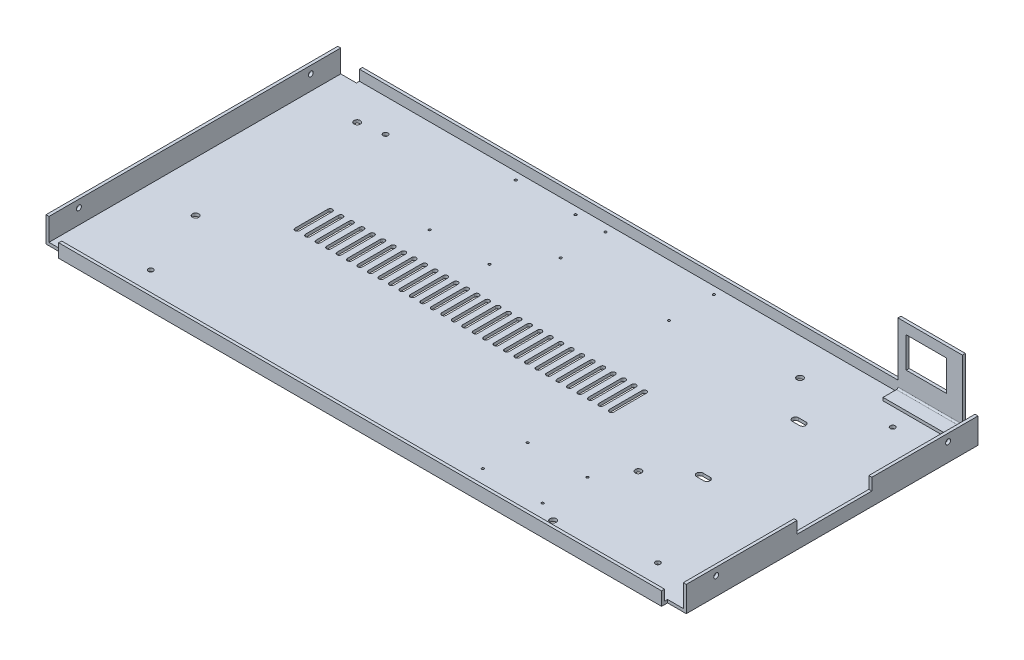
SolidWorks part; units mm, degrees
material "1023 Листовая углеродистая сталь (SS)"
ref_plane "Спереди" through (0, 0, 0) normal (0, 0, 1) x (1, 0, 0)
ref_plane "Сверху" through (0, 0, 0) normal (0, 1, 0) x (1, 0, 0)
ref_plane "Справа" through (0, 0, 0) normal (1, 0, 0) x (0, 0, -1)
sketch "Эскиз1" plane through (0, 0, 0) normal (0, 1, 0) x (1, 0, 0)
  line L0 (201.5, 101.5) -> (201.5, 97.5)
  line L1 (-201.5, -101.5) -> (201.5, -101.5)
  line L2 (-214, -97.5) -> (-214, 97.5)
  line L3 (-201.5, 101.5) -> (201.5, 101.5)
  line L4 (214, -97.5) -> (214, 97.5)
  line L7 (201.5, 97.5) -> (214, 97.5)
  line L8 (0, 152.6822) -> (0, -152.6822) construction
  line L9 (-278.6038, 0) -> (278.6038, 0) construction
  line L10 (201.5, -101.5) -> (201.5, -97.5)
  line L11 (201.5, -97.5) -> (214, -97.5)
  line L12 (-201.5, 101.5) -> (-201.5, 97.5)
  line L13 (-201.5, 97.5) -> (-214, 97.5)
  line L14 (-201.5, -101.5) -> (-201.5, -97.5)
  line L15 (-201.5, -97.5) -> (-214, -97.5)
  point P0 (0, 0)
  dimension "D3" = 4
  dimension "D4" = 12.5
extrude "Бобышка-Вытянуть2" add sketch "Эскиз1" along normal blind 2 contours L3 L0 L7 L4 L11 L10 L1 L14 L15 L2 L13 L12
sketch "Эскиз4" plane through (0, 2, 0) normal (0, 1, 0) x (1, 0, 0)
  line L0 (-138, 15) -> (-138, -7)
  line L1 (-135, 15) -> (-135, -7)
  line L2 (-214, -97.5) -> (-214, 97.5) construction
  line L3 (-201.5, 101.5) -> (201.5, 101.5) construction
  line L4 (-131, 15) -> (-131, -7)
  line L5 (-128, 15) -> (-128, -7)
  line L6 (-124, 15) -> (-124, -7)
  line L7 (-121, 15) -> (-121, -7)
  line L8 (-117, 15) -> (-117, -7)
  line L9 (-114, 15) -> (-114, -7)
  line L10 (-110, 15) -> (-110, -7)
  line L11 (-107, 15) -> (-107, -7)
  line L12 (-103, 15) -> (-103, -7)
  line L13 (-100, 15) -> (-100, -7)
  line L14 (-96, 15) -> (-96, -7)
  line L15 (-93, 15) -> (-93, -7)
  line L16 (-89, 15) -> (-89, -7)
  line L17 (-86, 15) -> (-86, -7)
  line L18 (-82, 15) -> (-82, -7)
  line L19 (-79, 15) -> (-79, -7)
  line L20 (-75, 15) -> (-75, -7)
  line L21 (-72, 15) -> (-72, -7)
  line L22 (-68, 15) -> (-68, -7)
  line L23 (-65, 15) -> (-65, -7)
  line L24 (-61, 15) -> (-61, -7)
  line L25 (-58, 15) -> (-58, -7)
  line L26 (-54, 15) -> (-54, -7)
  line L27 (-51, 15) -> (-51, -7)
  line L28 (-47, 15) -> (-47, -7)
  line L29 (-44, 15) -> (-44, -7)
  line L30 (-40, 15) -> (-40, -7)
  line L31 (-37, 15) -> (-37, -7)
  line L32 (-33, 15) -> (-33, -7)
  line L33 (-30, 15) -> (-30, -7)
  line L34 (-26, 15) -> (-26, -7)
  line L35 (-23, 15) -> (-23, -7)
  line L36 (-19, 15) -> (-19, -7)
  line L37 (-16, 15) -> (-16, -7)
  line L38 (-12, 15) -> (-12, -7)
  line L39 (-9, 15) -> (-9, -7)
  line L40 (-5, 15) -> (-5, -7)
  line L41 (-2, 15) -> (-2, -7)
  line L42 (2, 15) -> (2, -7)
  line L43 (5, 15) -> (5, -7)
  line L44 (9, 15) -> (9, -7)
  line L45 (12, 15) -> (12, -7)
  line L46 (16, 15) -> (16, -7)
  line L47 (19, 15) -> (19, -7)
  line L48 (23, 15) -> (23, -7)
  line L49 (26, 15) -> (26, -7)
  line L50 (30, 15) -> (30, -7)
  line L51 (33, 15) -> (33, -7)
  line L52 (37, 15) -> (37, -7)
  line L53 (40, 15) -> (40, -7)
  line L54 (44, 15) -> (44, -7)
  line L55 (47, 15) -> (47, -7)
  line L56 (51, 15) -> (51, -7)
  line L57 (54, 15) -> (54, -7)
  line L58 (58, 15) -> (58, -7)
  line L59 (61, 15) -> (61, -7)
  line L60 (65, 15) -> (65, -7)
  line L61 (68, 15) -> (68, -7)
  line L62 (72, 15) -> (72, -7)
  line L63 (75, 15) -> (75, -7)
  arc A0 (-138, 15) -> (-135, 15) centre (-136.5, 15) cw
  arc A1 (-135, -7) -> (-138, -7) centre (-136.5, -7) cw
  arc A2 (-131, 15) -> (-128, 15) centre (-129.5, 15) cw
  arc A3 (-128, -7) -> (-131, -7) centre (-129.5, -7) cw
  arc A4 (-124, 15) -> (-121, 15) centre (-122.5, 15) cw
  arc A5 (-121, -7) -> (-124, -7) centre (-122.5, -7) cw
  arc A6 (-117, 15) -> (-114, 15) centre (-115.5, 15) cw
  arc A7 (-114, -7) -> (-117, -7) centre (-115.5, -7) cw
  arc A8 (-110, 15) -> (-107, 15) centre (-108.5, 15) cw
  arc A9 (-107, -7) -> (-110, -7) centre (-108.5, -7) cw
  arc A10 (-103, 15) -> (-100, 15) centre (-101.5, 15) cw
  arc A11 (-100, -7) -> (-103, -7) centre (-101.5, -7) cw
  arc A12 (-96, 15) -> (-93, 15) centre (-94.5, 15) cw
  arc A13 (-93, -7) -> (-96, -7) centre (-94.5, -7) cw
  arc A14 (-89, 15) -> (-86, 15) centre (-87.5, 15) cw
  arc A15 (-86, -7) -> (-89, -7) centre (-87.5, -7) cw
  arc A16 (-82, 15) -> (-79, 15) centre (-80.5, 15) cw
  arc A17 (-79, -7) -> (-82, -7) centre (-80.5, -7) cw
  arc A18 (-75, 15) -> (-72, 15) centre (-73.5, 15) cw
  arc A19 (-72, -7) -> (-75, -7) centre (-73.5, -7) cw
  arc A20 (-68, 15) -> (-65, 15) centre (-66.5, 15) cw
  arc A21 (-65, -7) -> (-68, -7) centre (-66.5, -7) cw
  arc A22 (-61, 15) -> (-58, 15) centre (-59.5, 15) cw
  arc A23 (-58, -7) -> (-61, -7) centre (-59.5, -7) cw
  arc A24 (-54, 15) -> (-51, 15) centre (-52.5, 15) cw
  arc A25 (-51, -7) -> (-54, -7) centre (-52.5, -7) cw
  arc A26 (-47, 15) -> (-44, 15) centre (-45.5, 15) cw
  arc A27 (-44, -7) -> (-47, -7) centre (-45.5, -7) cw
  arc A28 (-40, 15) -> (-37, 15) centre (-38.5, 15) cw
  arc A29 (-37, -7) -> (-40, -7) centre (-38.5, -7) cw
  arc A30 (-33, 15) -> (-30, 15) centre (-31.5, 15) cw
  arc A31 (-30, -7) -> (-33, -7) centre (-31.5, -7) cw
  arc A32 (-26, 15) -> (-23, 15) centre (-24.5, 15) cw
  arc A33 (-23, -7) -> (-26, -7) centre (-24.5, -7) cw
  arc A34 (-19, 15) -> (-16, 15) centre (-17.5, 15) cw
  arc A35 (-16, -7) -> (-19, -7) centre (-17.5, -7) cw
  arc A36 (-12, 15) -> (-9, 15) centre (-10.5, 15) cw
  arc A37 (-9, -7) -> (-12, -7) centre (-10.5, -7) cw
  arc A38 (-5, 15) -> (-2, 15) centre (-3.5, 15) cw
  arc A39 (-2, -7) -> (-5, -7) centre (-3.5, -7) cw
  arc A40 (2, 15) -> (5, 15) centre (3.5, 15) cw
  arc A41 (5, -7) -> (2, -7) centre (3.5, -7) cw
  arc A42 (9, 15) -> (12, 15) centre (10.5, 15) cw
  arc A43 (12, -7) -> (9, -7) centre (10.5, -7) cw
  arc A44 (16, 15) -> (19, 15) centre (17.5, 15) cw
  arc A45 (19, -7) -> (16, -7) centre (17.5, -7) cw
  arc A46 (23, 15) -> (26, 15) centre (24.5, 15) cw
  arc A47 (26, -7) -> (23, -7) centre (24.5, -7) cw
  arc A48 (30, 15) -> (33, 15) centre (31.5, 15) cw
  arc A49 (33, -7) -> (30, -7) centre (31.5, -7) cw
  arc A50 (37, 15) -> (40, 15) centre (38.5, 15) cw
  arc A51 (40, -7) -> (37, -7) centre (38.5, -7) cw
  arc A52 (44, 15) -> (47, 15) centre (45.5, 15) cw
  arc A53 (47, -7) -> (44, -7) centre (45.5, -7) cw
  arc A54 (51, 15) -> (54, 15) centre (52.5, 15) cw
  arc A55 (54, -7) -> (51, -7) centre (52.5, -7) cw
  arc A56 (58, 15) -> (61, 15) centre (59.5, 15) cw
  arc A57 (61, -7) -> (58, -7) centre (59.5, -7) cw
  arc A58 (65, 15) -> (68, 15) centre (66.5, 15) cw
  arc A59 (68, -7) -> (65, -7) centre (66.5, -7) cw
  arc A60 (72, 15) -> (75, 15) centre (73.5, 15) cw
  arc A61 (75, -7) -> (72, -7) centre (73.5, -7) cw
  point P6 (-136.5, 16.5)
  point P7 (-136.5, -8.5)
  dimension "D1" = 25
  dimension "D2" = 3
  dimension "D3" = 76
  dimension "D4" = 85
  dimension "D5" = 31
extrude "Вырез-Вытянуть2" cut sketch "Эскиз4" against normal through all
sketch "Эскиз5" plane through (0, 2, 0) normal (0, 1, 0) x (1, 0, 0)
  line L1 (158.5, 101.5) -> (-201.5, 101.5)
  line L2 (158.5, 101.5) -> (158.5, 99.5)
  line L3 (158.5, 99.5) -> (-201.5, 99.5)
  line L4 (-201.5, 101.5) -> (-201.5, 99.5)
  line L5 (-201.5, 101.5) -> (-201.5, 97.5) construction
  line L6 (-201.5, -101.5) -> (-201.5, -97.5) construction
  line L7 (201.5, -101.5) -> (-201.5, -101.5)
  line L8 (201.5, -101.5) -> (201.5, -99.5)
  line L9 (201.5, -99.5) -> (-201.5, -99.5)
  line L10 (-201.5, -101.5) -> (-201.5, -99.5)
  line L12 (-201.5, 101.5) -> (201.5, 101.5) construction
  line L13 (201.5, 101.5) -> (201.5, 97.5) construction
  dimension "D1" = 2
  dimension "D2" = 43
extrude "Передний-задний буртики" add sketch "Эскиз5" along normal blind 7
sketch "Эскиз6" plane through (0, 2, 0) normal (0, 1, 0) x (1, 0, 0)
  line L0 (-201.5, 97.5) -> (-214, 97.5) construction
  line L1 (-214, -97.5) -> (-212, -97.5)
  line L2 (-214, -97.5) -> (-214, 97.5)
  line L3 (-214, 97.5) -> (-212, 97.5)
  line L4 (-212, -97.5) -> (-212, 97.5)
  line L5 (201.5, -97.5) -> (214, -97.5) construction
  line L6 (214, 97.5) -> (212, 97.5)
  line L7 (214, 97.5) -> (214, -97.5)
  line L8 (214, -97.5) -> (212, -97.5)
  line L9 (212, 97.5) -> (212, -97.5)
  dimension "D1" = 2
  dimension "D2" = 2
extrude "левый-правый буртики" add sketch "Эскиз6" along normal blind 15
sketch "Эскиз7" plane through (214, 0, 0) normal (1, 0, 0) x (0, 0, -1)
  line L0 (-97.5, 17) -> (97.5, 17) construction
  line L1 (-23.5, 9) -> (26.5, 9)
  line L2 (-23.5, 9) -> (-23.5, 17)
  line L3 (-23.5, 17) -> (26.5, 17)
  line L4 (26.5, 9) -> (26.5, 17)
  line L5 (97.5, 17) -> (97.5, 0) construction
  dimension "D1" = 8
  dimension "D2" = 50
  dimension "D3" = 71
extrude "Вырез-Вытянуть3" cut sketch "Эскиз7" against normal up to next
sketch "Эскиз9" plane through (158.5, 0, 0) normal (1, 0, 0) x (0, 0, -1)
  line L0 (100, 2) -> (89.5, 2)
  line L1 (89.5, 2) -> (89.5, 4)
  line L2 (89.5, 4) -> (98.5, 4)
  line L3 (99.5, 9) -> (99.5, 2) construction
  line L4 (99.5, 5) -> (99.5, 45)
  line L5 (99.5, 45) -> (101.5, 45)
  line L6 (101.5, 45) -> (101.5, 3.5)
  arc A0 (100, 2) -> (101.5, 3.5) centre (100, 3.5) ccw
  arc A1 (98.5, 4) -> (99.5, 5) centre (98.5, 5) ccw
  point P8 (101.5, 2)
  dimension "D3" = 1.5
  dimension "D4" = 1
  dimension "D1" = 2
  dimension "D2" = 43
  dimension "D5" = 12
extrude "Бобышка-Вытянуть5" add sketch "Эскиз9" along normal blind 43
sketch "Эскиз10" plane through (0, 2, 0) normal (0, 1, 0) x (1, 0, 0)
  line L0 (-201.5, -101.5) -> (201.5, -101.5) construction
  line L1 (-214, 97.5) -> (-214, -97.5) construction
  point P0 (117.5, 75)
  point P1 (117.5, -33)
  point P2 (117.5, -90)
  point P3 (-178.5, 75)
  point P4 (-178.5, -33)
  dimension "D1" = 296
  dimension "D2" = 108
  dimension "D3" = 57
  dimension "D4" = 11.5
  dimension "D5" = 35.5
hole_wizard "Под редуктор" positions "Эскиз11" profile "Эскиз12" hole size "M4x0.7" standard "DIN" end condition through all
sketch "Эскиз11" plane through (0, 2, 0) normal (0, 1, 0) x (1, 0, 0)
  point P0 (-178.5, 75)
  point P3 (-178.5, -33)
  point P6 (117.5, -33)
  point P9 (117.5, -90)
  point P12 (117.5, 75)
sketch "Эскиз12" plane through (-178.5, 2, -75) normal (1, 0, 0) x (0, 0, 1)
  line L0 (0, 0) -> (0, 2)
  line L1 (0, 2) -> (2.1, 2)
  line L2 (2.1, 2) -> (2.1, 0)
  line L5 (2.1, 0) -> (0, 0)
  line L11 (0, -6.35) -> (0, 107.95) construction
  dimension "Диаметр сквозного отверстия" = 4.2
  dimension "Глубина сквозного отверстия" = 2
sketch "Эскиз13" plane through (0, 2, 0) normal (0, 1, 0) x (1, 0, 0)
  line L0 (140.1, 51.5) -> (144.9, 51.5)
  line L1 (140.1, 47.3) -> (144.9, 47.3)
  line L2 (61, 17.4) -> (237.4964, 17.4) construction
  line L3 (140.1, -12.5) -> (144.9, -12.5)
  line L4 (140.1, -16.7) -> (144.9, -16.7)
  line L5 (158.5, 101.5) -> (-201.5, 101.5) construction
  line L6 (214, 26.5) -> (214, 97.5) construction
  arc A0 (144.9, 51.5) -> (144.9, 47.3) centre (144.9, 49.4) cw
  arc A1 (140.1, 51.5) -> (140.1, 47.3) centre (140.1, 49.4) ccw
  arc A2 (140.1, -16.7) -> (140.1, -12.5) centre (140.1, -14.6) cw
  arc A3 (144.9, -16.7) -> (144.9, -12.5) centre (144.9, -14.6) ccw
  point P8 (138, 49.4)
  point P9 (147, 49.4)
  dimension "D1" = 4.2
  dimension "D2" = 9
  dimension "D3" = 29.9
  dimension "D4" = 50
  dimension "D5" = 67
extrude "Под двигатель" cut sketch "Эскиз13" against normal through all
sketch "Эскиз14" plane through (214, 0, 0) normal (1, 0, 0) x (0, 0, -1)
  line L0 (-97.5, 17) -> (-97.5, 0) construction
  line L1 (97.5, 17) -> (97.5, 0) construction
  line L2 (26.5, 17) -> (97.5, 17) construction
  point P0 (77.5, 12)
  point P1 (-77.5, 12)
  dimension "D1" = 20
  dimension "D2" = 20
  dimension "D3" = 5
hole_wizard "Отверстие обработанное метчиком M41" positions "Эскиз15" profile "Эскиз16" tap size "M4" standard "DIN" end condition through all
sketch "Эскиз15" plane through (214, 0, 0) normal (1, 0, 0) x (0, 0, -1)
  point P0 (77.5, 12)
  point P3 (-77.5, 12)
sketch "Эскиз16" plane through (214, 12, -77.5) normal (0, 1, 0) x (0, 0, -1)
  line L0 (0, 0) -> (0, 428)
  line L1 (0, 428) -> (1.65, 428)
  line L2 (1.65, 428) -> (1.65, 0)
  line L5 (1.65, 0) -> (0, 0)
  line L11 (0, -6.35) -> (0, 107.95) construction
  dimension "Диаметр проходного сверла" = 3.3
  dimension "Глубина проходного сверла" = 428
cosmetic thread "Отверстие резьбы1" parameters "D2"=4
cosmetic thread "Отверстие резьбы2" parameters "D2"=4
sketch "Эскиз17" plane through (0, 0, 0) normal (0, -1, 0) x (1, 0, 0)
  line L0 (-214, 97.5) -> (-214, -97.5) construction
  line L1 (177, -77.5) -> (-162, -77.5) construction
  line L2 (177, -77.5) -> (177, 79.5) construction
  line L3 (177, 79.5) -> (-162, 79.5) construction
  line L4 (-162, -77.5) -> (-162, 79.5) construction
  line L5 (-201.5, -101.5) -> (201.5, -101.5) construction
  dimension "D1" = 157
  dimension "D2" = 339
  dimension "D3" = 52
  dimension "D4" = 24
hole_wizard "Отверстие обработанное метчиком M42" positions "Эскиз18" profile "Эскиз19" tap size "M4" standard "DIN" end condition through all
sketch "Эскиз18" plane through (0, 0, 0) normal (0, -1, 0) x (-1, 0, 0)
  point P0 (-177, 77.5)
  point P3 (-177, -79.5)
  point P6 (162, -79.5)
  point P9 (162, 77.5)
sketch "Эскиз19" plane through (177, 0, -77.5) normal (1, 0, 0) x (0, 0, -1)
  line L0 (0, 0) -> (0, 45)
  line L1 (0, 45) -> (1.65, 45)
  line L2 (1.65, 45) -> (1.65, 0)
  line L5 (1.65, 0) -> (0, 0)
  line L11 (0, -6.35) -> (0, 107.95) construction
  dimension "Диаметр проходного сверла" = 3.3
  dimension "Глубина проходного сверла" = 45
cosmetic thread "Отверстие резьбы3" parameters "D2"=4
cosmetic thread "Отверстие резьбы4" parameters "D2"=4
cosmetic thread "Отверстие резьбы5" parameters "D2"=4
cosmetic thread "Отверстие резьбы6" parameters "D2"=4
sketch "Эскиз20" plane through (0, 2, 0) normal (0, 1, 0) x (1, 0, 0)
  line L1 (-92, 94.5) -> (-52, 94.5)
  line L2 (-92, 94.5) -> (-92, 37)
  line L3 (-92, 37) -> (-52, 37)
  line L4 (-52, 94.5) -> (-52, 37)
  line L5 (-201.5, 99.5) -> (158.5, 99.5) construction
  line L6 (-212, -97.5) -> (-212, 97.5) construction
  line L8 (-32, 64.5) -> (40.5, 64.5)
  line L9 (-32, 64.5) -> (-32, 94.5)
  line L10 (-32, 94.5) -> (40.5, 94.5)
  line L11 (40.5, 64.5) -> (40.5, 94.5)
  line L12 (64, -83.5) -> (104, -83.5)
  line L13 (64, -83.5) -> (64, -53.5)
  line L14 (64, -53.5) -> (104, -53.5)
  line L15 (104, -83.5) -> (104, -53.5)
  line L16 (201.5, -99.5) -> (-201.5, -99.5) construction
  line L17 (-214, 97.5) -> (-214, -97.5) construction
  point P20 (0, 0)
  dimension "D1" = 57.5
  dimension "D2" = 40
  dimension "D3" = 5
  dimension "D4" = 120
  dimension "D5" = 72.5
  dimension "D6" = 30
  dimension "D7" = 20
  dimension "D8" = 30
  dimension "D9" = 40
  dimension "D10" = 318
  dimension "D11" = 16
hole_wizard "Отверстие обработанное метчиком M21" positions "Эскиз21" profile "Эскиз22" tap size "M2" standard "DIN" end condition through all
sketch "Эскиз21" plane through (0, 2, 0) normal (0, 1, 0) x (1, 0, 0)
  point P0 (-92, 94.5)
  point P3 (-52, 94.5)
  point P6 (-52, 37)
  point P9 (-92, 37)
  point P12 (-32, 64.5)
  point P15 (-32, 94.5)
  point P18 (40.5, 94.5)
  point P21 (40.5, 64.5)
  point P24 (64, -53.5)
  point P27 (64, -83.5)
  point P30 (104, -83.5)
  point P33 (104, -53.5)
sketch "Эскиз22" plane through (-92, 2, -94.5) normal (1, 0, 0) x (0, 0, 1)
  line L0 (0, 0) -> (0, 2)
  line L1 (0, 2) -> (0.8, 2)
  line L2 (0.8, 2) -> (0.8, 0)
  line L5 (0.8, 0) -> (0, 0)
  line L11 (0, -6.35) -> (0, 107.95) construction
  dimension "Диаметр проходного сверла" = 1.6
  dimension "Глубина проходного сверла" = 2
cosmetic thread "Отверстие резьбы7" parameters "D2"=2
cosmetic thread "Отверстие резьбы8" parameters "D2"=2
cosmetic thread "Отверстие резьбы9" parameters "D2"=2
cosmetic thread "Отверстие резьбы10" parameters "D2"=2
cosmetic thread "Отверстие резьбы11" parameters "D2"=2
cosmetic thread "Отверстие резьбы12" parameters "D2"=2
cosmetic thread "Отверстие резьбы13" parameters "D2"=2
cosmetic thread "Отверстие резьбы14" parameters "D2"=2
cosmetic thread "Отверстие резьбы15" parameters "D2"=2
cosmetic thread "Отверстие резьбы16" parameters "D2"=2
cosmetic thread "Отверстие резьбы17" parameters "D2"=2
cosmetic thread "Отверстие резьбы18" parameters "D2"=2
sketch "Эскиз23" plane through (0, 0, -101.5) normal (0, 0, -1) x (-1, 0, 0)
  line L0 (-164, 40) -> (-191, 40) construction
  line L1 (-191, 38) -> (-164, 38)
  line L2 (-191, 38) -> (-191, 17.5)
  line L3 (-191, 17.5) -> (-164, 17.5)
  line L4 (-164, 38) -> (-164, 17.5)
  point P6 (-177.5, 40)
  point P7 (-177.5, 38)
  dimension "D1" = 27
  dimension "D2" = 20.5
  dimension "D3" = 2
extrude "Вырез-Вытянуть4" cut sketch "Эскиз23" against normal up to next
